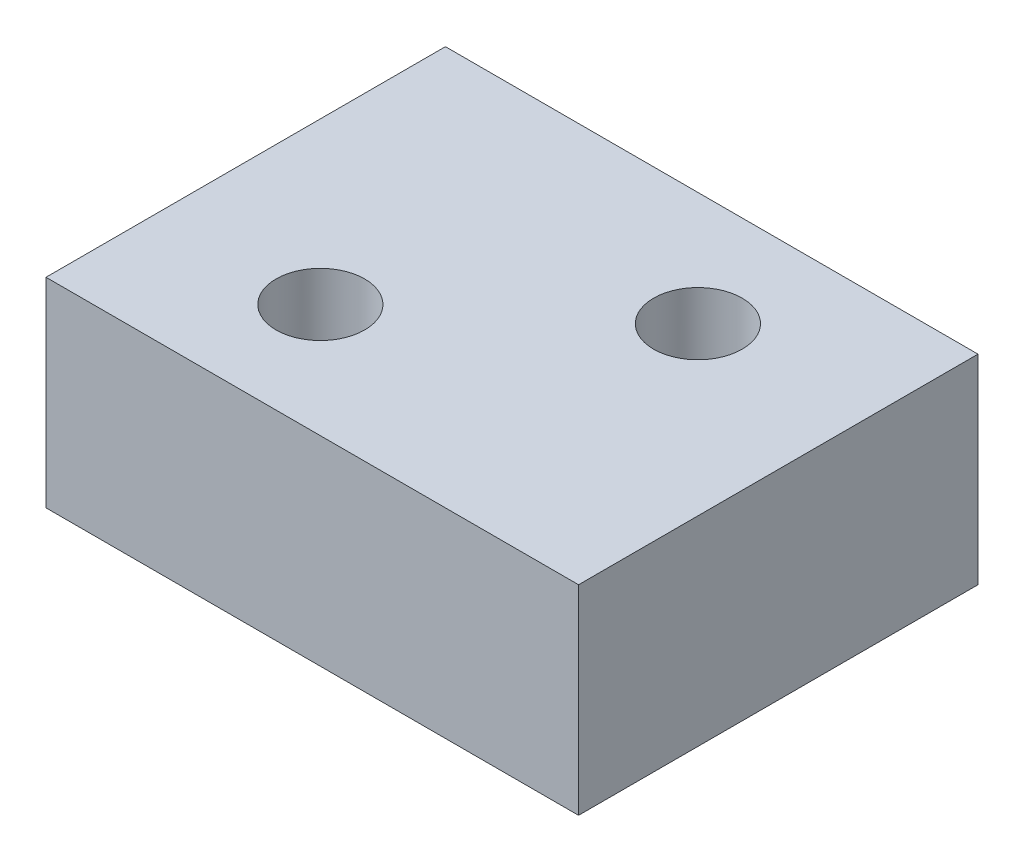
SolidWorks part; units mm, degrees
ref_plane "Front Plane" through (0, 0, 0) normal (0, 0, 1) x (1, 0, 0)
ref_plane "Top Plane" through (0, 0, 0) normal (0, 1, 0) x (1, 0, 0)
ref_plane "Right Plane" through (0, 0, 0) normal (1, 0, 0) x (0, 0, -1)
sketch "Sketch1" plane through (0, 0, 0) normal (0, 1, 0) x (1, 0, 0)
  line L1 (-20, -15) -> (20, -15)
  line L2 (-20, -15) -> (-20, 15)
  line L3 (-20, 15) -> (20, 15)
  line L4 (20, -15) -> (20, 15)
  line L5 (-20, -15) -> (20, 15) construction
  line L6 (-20, 15) -> (20, -15) construction
  point P0 (0, 0)
  dimension "D1" = 40
  dimension "D2" = 30
extrude "Boss-Extrude1" add sketch "Sketch1" along normal blind 10
sketch "Sketch2" plane through (0, 0, 0) normal (0, -1, 0) x (-1, 0, 0)
  line L0 (0, -15) -> (0, 15) construction
  line L1 (20, -15) -> (-20, -15) construction
  line L2 (-20, 15) -> (20, 15) construction
  line L3 (20, 0) -> (-20, 0) construction
  line L4 (20, 15) -> (20, -15) construction
  line L5 (-20, -15) -> (-20, 15) construction
  line L6 (20, -15) -> (-20, 15) construction
  line L7 (-20, -15) -> (20, 15) construction
  circle A0 centre (-13.3333, -10) radius 2
  circle A1 centre (13.3333, -10) radius 2
  circle A2 centre (-13.3333, 10) radius 2
  circle A3 centre (13.3333, 10) radius 2
  dimension "D1" = 4
  dimension "D2" = 5
extrude "Cut-Extrude1" cut sketch "Sketch2" against normal blind 5
sketch "Sketch3" plane through (0, 10, 0) normal (0, 1, 0) x (1, 0, 0)
  line L0 (20, -15) -> (20, 15) construction
  line L4 (-20, -15) -> (20, -15) construction
  line L8 (7.5, -6.465) -> (7.5, 6.4636) construction
  line L11 (-20, 15) -> (-20, -15) construction
  circle A0 centre (-7.9286, -6.465) radius 4.8125
  circle A1 centre (7.5, 6.4636) radius 4.8125
  dimension "D1" = 9.625
  dimension "D3" = 8.535
  dimension "D6" = 9.625
  dimension "D2" = 12.0714
  dimension "D4" = 12.5
  dimension "D5" = 12.9286
extrude "Cut-Extrude2" cut sketch "Sketch3" against normal blind 4
sketch "Sketch4" plane through (0, 6, 0) normal (0, 1, 0) x (1, 0, 0)
  circle A0 centre (-7.9286, -6.465) radius 3.325
  circle A1 centre (7.5, 6.4636) radius 3.325
  dimension "D1" = 6.65
  dimension "D2" = 6.65
sketch "Sketch5" plane through (0, 10, 0) normal (0, 1, 0) x (1, 0, 0)
  line L1 (-20, -15) -> (20, -15)
  line L2 (-20, -15) -> (-20, 15)
  line L3 (-20, 15) -> (20, 15)
  line L4 (20, -15) -> (20, 15)
extrude "Boss-Extrude2" add sketch "Sketch5" along normal blind 5
extrude "Cut-Extrude3" cut sketch "Sketch4" against normal blind 1 and the other way through all
